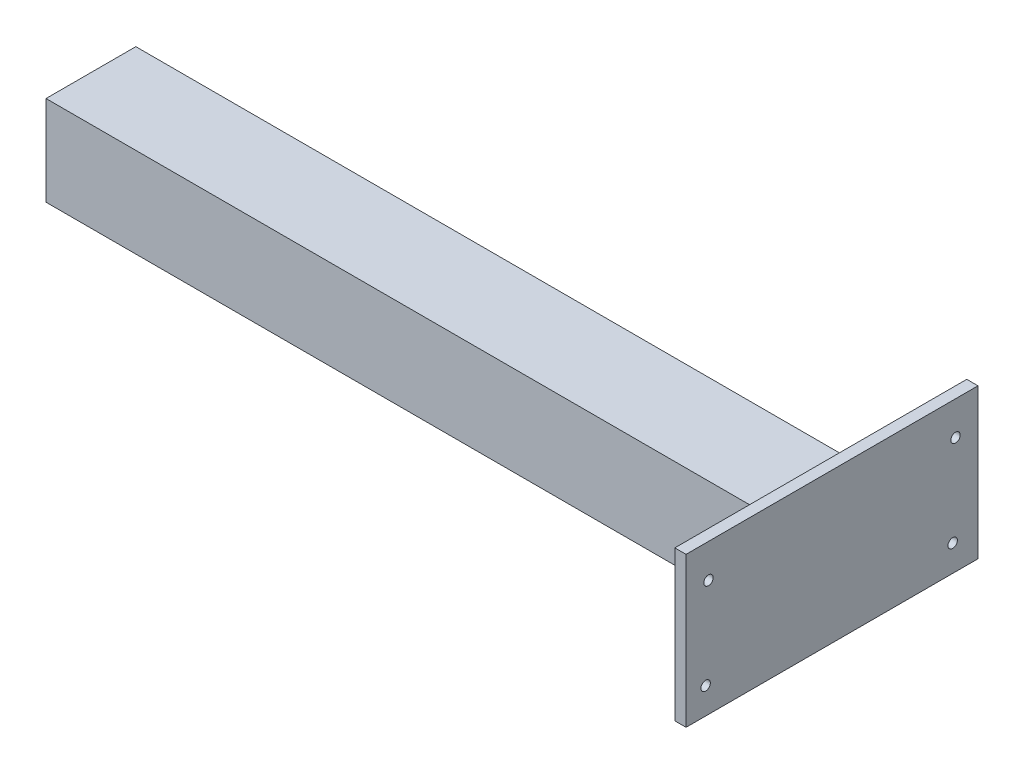
SolidWorks part; units mm, degrees
ref_plane "前视基准面" through (0, 0, 0) normal (0, 0, 1) x (1, 0, 0)
ref_plane "上视基准面" through (0, 0, 0) normal (0, 1, 0) x (1, 0, 0)
ref_plane "右视基准面" through (0, 0, 0) normal (1, 0, 0) x (0, 0, -1)
other "Configuration Table"
sketch "草图1" plane through (0, 0, 0) normal (0, 0, 1) x (1, 0, 0)
  line L1 (-200, 20) -> (200, 20)
  line L2 (-200, 20) -> (-200, -20)
  line L3 (-200, -20) -> (200, -20)
  line L4 (200, 20) -> (200, -20)
  line L5 (-200, 20) -> (200, -20) construction
  line L6 (-200, -20) -> (200, 20) construction
  point P0 (0, 0)
  dimension "D1" = 400
  dimension "D2" = 40
extrude "凸台-拉伸1" add sketch "草图1" against normal blind 40
sketch "草图2" plane through (200, 0, 0) normal (1, 0, 0) x (0, 0, -1)
  line L5 (40, -20) -> (40, 20) construction
  line L6 (40, -10) -> (51, -10)
  line L9 (46, -5) -> (51, -5)
  line L10 (46, -5) -> (46, -10)
  line L11 (46, -10) -> (51, -10)
  line L12 (51, -5) -> (51, -10)
  line L13 (46, -5) -> (51, -10) construction
  line L14 (46, -10) -> (51, -5) construction
  line L20 (40, -10) -> (40, -20)
  line L21 (40, -20) -> (51, -20)
  line L22 (51, -10) -> (51, -20)
  line L23 (40, -10) -> (51, -20) construction
  line L24 (40, -20) -> (51, -10) construction
  line L25 (40, -20) -> (0, -20) construction
  point P0 (45.5, -15)
  point P12 (48.5, -7.5)
  dimension "D1" = 11
  dimension "D2" = 10
  dimension "D3" = 5
  dimension "D4" = 5
extrude "凸台-拉伸2" add sketch "草图2" against normal blind 400 contours L20 L6 L22 L21
sketch "草图10" plane through (200, 0, 0) normal (1, 0, 0) x (0, 0, -1)
  line L0 (0, 20) -> (20, 20)
  line L1 (40, 20) -> (0, 20) construction
  line L2 (20, 20) -> (20, 0)
  line L3 (20, 0) -> (70, 0)
  line L4 (70, 0) -> (70, 46.72)
  line L5 (70, 0) -> (70, -47.28)
  line L6 (70, -47.28) -> (-60, -47.28)
  line L7 (-60, -47.28) -> (-60, 46.72)
  line L8 (-60, 46.72) -> (70, 46.72)
extrude "凸台-拉伸4" add sketch "草图10" along normal blind 5 contours L5 L6 L7 L8 L4
sketch "草图12" plane through (200, 0, 0) normal (-1, 0, 0) x (0, 0, 1)
  line L0 (60, 46.72) -> (10, 46.72)
  line L2 (60, 46.72) -> (-70, 46.72) construction
  line L6 (10, 46.72) -> (10, 1.72)
  line L7 (10, 1.72) -> (50, 1.72)
  line L8 (50, 1.72) -> (50, 31.72)
  line L9 (50, 1.72) -> (50, -28.28)
  line L10 (50, -28.28) -> (-60, -28.28)
  line L11 (50, 31.72) -> (-60, 31.72)
  circle A0 centre (10, 1.72) radius 2.0061
  circle A1 centre (-60, 31.72) radius 2.017
  point P7 (50, 31.72)
  point P11 (50, -28.28)
  point P12 (-60, -28.28)
  point P13 (-60, 31.72)
hole_wizard "Ø4.2 (4.2) 直径孔1" positions "草图12" profile "草图13" hole size "Ø4.2" standard "ISO" end condition through all
sketch "草图13" plane through (200, 31.72, -60) normal (0, 1, 0) x (0, 0, 1)
  line L0 (0, 0) -> (0, 5)
  line L1 (0, 5) -> (2.1, 5)
  line L2 (2.1, 5) -> (2.1, 0)
  line L5 (2.1, 0) -> (0, 0)
  line L11 (0, -6.35) -> (0, 107.95) construction
  dimension "通孔孔直径" = 4.2
  dimension "通孔孔深度" = 5
sketch "草图17" plane through (0, 0, 0) normal (0, 0, 1) x (1, 0, 0)
  line L0 (-200, 20) -> (-150, 20)
  line L1 (200, 20) -> (-200, 20) construction
  line L2 (-150, 20) -> (-150, -20)
  line L3 (-200, -20) -> (200, -20) construction
  line L4 (-150, -20) -> (-200, -20)
  line L5 (-200, -20) -> (-200, 20)
extrude "切除-拉伸5" cut sketch "草图17" against normal blind 50
sketch "草图22" plane through (200, 0, 0) normal (-1, 0, 0) x (0, 0, 1)
  line L0 (-70, -20.1264) -> (60, -20.1264)
  line L1 (-70, 46.72) -> (-70, -47.28) construction
  line L2 (-70, -20.1264) -> (-70, -47.28)
  line L3 (-70, -47.28) -> (60, -47.28)
  line L4 (60, -47.28) -> (60, -20.1264)
extrude "切除-拉伸11" cut sketch "草图22" against normal blind 10
hole_wizard "Ø1.0 (4.2) 直径孔1" positions "草图25" profile "草图26" hole size "Ø1.0" standard "ISO" end condition through all
sketch "草图25" plane through (200, 0, 0) normal (-1, 0, 0) x (0, 0, 1)
  point P0 (51.2755, -8.28)
  point P2 (50, 31.72)
  point P5 (-60, 31.72)
  point P8 (-58.7245, -8.28)
  dimension "D1" = 40
  dimension "D2" = 40
  dimension "D3" = 110
sketch "草图26" plane through (200, -8.28, 51.2755) normal (0, 1, 0) x (0, 0, 1)
  line L0 (0, 0) -> (0, 5)
  line L1 (0, 5) -> (2.1, 5)
  line L2 (2.1, 5) -> (2.1, 0)
  line L5 (2.1, 0) -> (0, 0)
  line L11 (0, -6.35) -> (0, 107.95) construction
  dimension "通孔孔直径" = 4.2
  dimension "通孔孔深度" = 5
sketch "草图30" plane through (0, -10, 0) normal (0, 1, 0) x (1, 0, 0)
  line L0 (-150, 50) -> (-150, 51)
  line L1 (-200, 51) -> (200, 51) construction
  line L2 (-150, 51) -> (-200, 51)
  line L3 (-200, 51) -> (-200, 50)
  line L4 (-200, 50) -> (-150, 50) construction
  line L5 (-200, 50) -> (-150, 50)
extrude "切除-拉伸13" cut sketch "草图30" against normal blind 10
sketch "草图31" plane through (200, 0, 0) normal (-1, 0, 0) x (0, 0, 1)
  line L4 (-51, -10) -> (-43, -10)
  line L5 (-51, -10) -> (-51, 0)
  line L7 (-40, -10) -> (-51, -10) construction
  line L8 (-43, -10) -> (-43, 0)
  line L9 (-43, 0) -> (-51, 0)
extrude "凸台-拉伸6" add sketch "草图31" along normal blind 350
sketch "草图32" plane through (0, 0, -51) normal (0, 0, -1) x (-1, 0, 0)
  line L1 (-65.3449, -4.7056) -> (-63.3449, -4.7056)
  line L3 (-198.5883, -4.7056) -> (-196.5883, -4.7056)
  line L4 (-200, 0) -> (-195.1766, 0)
  line L5 (150, 0) -> (-200, 0) construction
  line L6 (-195.1766, 0) -> (-196.5883, -4.7056)
  line L7 (-198.5883, -4.7056) -> (-200, 0)
  line L8 (-191.5346, -4.7056) -> (-189.5346, -4.7056)
  line L9 (-188.1229, 0) -> (-189.5346, -4.7056)
  line L10 (-192.9463, 0) -> (-188.1229, 0)
  line L11 (-191.5346, -4.7056) -> (-192.9463, 0)
  line L12 (-184.5256, -4.7056) -> (-182.5256, -4.7056)
  line L13 (-181.114, 0) -> (-182.5256, -4.7056)
  line L14 (-185.9373, 0) -> (-181.114, 0)
  line L15 (-184.5256, -4.7056) -> (-185.9373, 0)
  line L16 (-177.4719, -4.7056) -> (-175.4719, -4.7056)
  line L17 (-174.0602, 0) -> (-175.4719, -4.7056)
  line L18 (-178.8836, 0) -> (-174.0602, 0)
  line L19 (-177.4719, -4.7056) -> (-178.8836, 0)
  line L20 (-156.49, -4.7056) -> (-154.49, -4.7056)
  line L21 (-153.0783, 0) -> (-154.49, -4.7056)
  line L22 (-157.9017, 0) -> (-153.0783, 0)
  line L23 (-156.49, -4.7056) -> (-157.9017, 0)
  line L24 (-163.4989, -4.7056) -> (-161.4989, -4.7056)
  line L25 (-160.0873, 0) -> (-161.4989, -4.7056)
  line L26 (-164.9106, 0) -> (-160.0873, 0)
  line L27 (-163.4989, -4.7056) -> (-164.9106, 0)
  line L28 (-170.5527, -4.7056) -> (-168.5527, -4.7056)
  line L29 (-167.141, 0) -> (-168.5527, -4.7056)
  line L30 (-171.9644, 0) -> (-167.141, 0)
  line L31 (-170.5527, -4.7056) -> (-171.9644, 0)
  line L32 (-149.4363, -4.7056) -> (-147.4363, -4.7056)
  line L33 (-146.0246, 0) -> (-147.4363, -4.7056)
  line L34 (-150.848, 0) -> (-146.0246, 0)
  line L35 (-149.4363, -4.7056) -> (-150.848, 0)
  line L36 (-121.4206, -4.7056) -> (-119.4206, -4.7056)
  line L37 (-118.0089, 0) -> (-119.4206, -4.7056)
  line L38 (-122.8323, 0) -> (-118.0089, 0)
  line L39 (-121.4206, -4.7056) -> (-122.8323, 0)
  line L40 (-128.4743, -4.7056) -> (-126.4743, -4.7056)
  line L41 (-125.0626, 0) -> (-126.4743, -4.7056)
  line L42 (-129.886, 0) -> (-125.0626, 0)
  line L43 (-128.4743, -4.7056) -> (-129.886, 0)
  line L44 (-135.4833, -4.7056) -> (-133.4833, -4.7056)
  line L45 (-132.0716, 0) -> (-133.4833, -4.7056)
  line L46 (-136.8949, 0) -> (-132.0716, 0)
  line L47 (-135.4833, -4.7056) -> (-136.8949, 0)
  line L48 (-142.537, -4.7056) -> (-140.537, -4.7056)
  line L49 (-139.1253, 0) -> (-140.537, -4.7056)
  line L50 (-143.9487, 0) -> (-139.1253, 0)
  line L51 (-142.537, -4.7056) -> (-143.9487, 0)
  line L52 (-93.3984, -4.7056) -> (-91.3984, -4.7056)
  line L53 (-89.9867, 0) -> (-91.3984, -4.7056)
  line L54 (-94.8101, 0) -> (-89.9867, 0)
  line L55 (-93.3984, -4.7056) -> (-94.8101, 0)
  line L56 (-100.4522, -4.7056) -> (-98.4522, -4.7056)
  line L57 (-97.0405, 0) -> (-98.4522, -4.7056)
  line L58 (-101.8638, 0) -> (-97.0405, 0)
  line L59 (-100.4522, -4.7056) -> (-101.8638, 0)
  line L60 (-107.4611, -4.7056) -> (-105.4611, -4.7056)
  line L61 (-104.0494, 0) -> (-105.4611, -4.7056)
  line L62 (-108.8728, 0) -> (-104.0494, 0)
  line L63 (-107.4611, -4.7056) -> (-108.8728, 0)
  line L64 (-114.5148, -4.7056) -> (-112.5148, -4.7056)
  line L65 (-111.1031, 0) -> (-112.5148, -4.7056)
  line L66 (-115.9265, 0) -> (-111.1031, 0)
  line L67 (-114.5148, -4.7056) -> (-115.9265, 0)
  line L68 (-61.9332, 0) -> (-63.3449, -4.7056)
  line L69 (-66.7566, 0) -> (-61.9332, 0)
  line L70 (-65.3449, -4.7056) -> (-66.7566, 0)
  line L71 (-72.3986, -4.7056) -> (-70.3986, -4.7056)
  line L72 (-68.9869, 0) -> (-70.3986, -4.7056)
  line L73 (-73.8103, 0) -> (-68.9869, 0)
  line L74 (-72.3986, -4.7056) -> (-73.8103, 0)
  line L75 (-79.4076, -4.7056) -> (-77.4076, -4.7056)
  line L76 (-75.9959, 0) -> (-77.4076, -4.7056)
  line L77 (-80.8192, 0) -> (-75.9959, 0)
  line L78 (-79.4076, -4.7056) -> (-80.8192, 0)
  line L79 (-86.4613, -4.7056) -> (-84.4613, -4.7056)
  line L80 (-83.0496, 0) -> (-84.4613, -4.7056)
  line L81 (-87.873, 0) -> (-83.0496, 0)
  line L82 (-86.4613, -4.7056) -> (-87.873, 0)
  line L83 (-37.0463, -4.7056) -> (-35.0463, -4.7056)
  line L84 (-33.6346, 0) -> (-35.0463, -4.7056)
  line L85 (-38.458, 0) -> (-33.6346, 0)
  line L86 (-37.0463, -4.7056) -> (-38.458, 0)
  line L87 (-44.1001, -4.7056) -> (-42.1001, -4.7056)
  line L88 (-40.6884, 0) -> (-42.1001, -4.7056)
  line L89 (-45.5118, 0) -> (-40.6884, 0)
  line L90 (-44.1001, -4.7056) -> (-45.5118, 0)
  line L91 (-51.109, -4.7056) -> (-49.109, -4.7056)
  line L92 (-47.6973, 0) -> (-49.109, -4.7056)
  line L93 (-52.5207, 0) -> (-47.6973, 0)
  line L94 (-51.109, -4.7056) -> (-52.5207, 0)
  line L95 (-58.1627, -4.7056) -> (-56.1627, -4.7056)
  line L96 (-54.751, 0) -> (-56.1627, -4.7056)
  line L97 (-59.5744, 0) -> (-54.751, 0)
  line L98 (-58.1627, -4.7056) -> (-59.5744, 0)
  line L99 (-30.1435, -4.7056) -> (-28.1435, -4.7056)
  line L100 (-26.7318, 0) -> (-28.1435, -4.7056)
  line L101 (-31.5552, 0) -> (-26.7318, 0)
  line L102 (-30.1435, -4.7056) -> (-31.5552, 0)
  line L103 (-23.0897, -4.7056) -> (-21.0897, -4.7056)
  line L104 (-19.6781, 0) -> (-21.0897, -4.7056)
  line L105 (-24.5014, 0) -> (-19.6781, 0)
  line L106 (-23.0897, -4.7056) -> (-24.5014, 0)
  line L107 (-16.0808, -4.7056) -> (-14.0808, -4.7056)
  line L108 (-12.6691, 0) -> (-14.0808, -4.7056)
  line L109 (-17.4925, 0) -> (-12.6691, 0)
  line L110 (-16.0808, -4.7056) -> (-17.4925, 0)
  line L111 (-9.0271, -4.7056) -> (-7.0271, -4.7056)
  line L112 (-5.6154, 0) -> (-7.0271, -4.7056)
  line L113 (-10.4388, 0) -> (-5.6154, 0)
  line L114 (-9.0271, -4.7056) -> (-10.4388, 0)
  line L115 (-2.158, -4.7056) -> (-0.158, -4.7056)
  line L116 (1.2537, 0) -> (-0.158, -4.7056)
  line L117 (-3.5697, 0) -> (1.2537, 0)
  line L118 (-2.158, -4.7056) -> (-3.5697, 0)
  line L119 (4.8958, -4.7056) -> (6.8958, -4.7056)
  line L120 (8.3074, 0) -> (6.8958, -4.7056)
  line L121 (3.4841, 0) -> (8.3074, 0)
  line L122 (4.8958, -4.7056) -> (3.4841, 0)
  line L123 (11.9047, -4.7056) -> (13.9047, -4.7056)
  line L124 (15.3164, 0) -> (13.9047, -4.7056)
  line L125 (10.493, 0) -> (15.3164, 0)
  line L126 (11.9047, -4.7056) -> (10.493, 0)
  line L127 (18.9584, -4.7056) -> (20.9584, -4.7056)
  line L128 (22.3701, 0) -> (20.9584, -4.7056)
  line L129 (17.5467, 0) -> (22.3701, 0)
  line L130 (18.9584, -4.7056) -> (17.5467, 0)
  line L131 (46.9794, -4.7056) -> (48.9794, -4.7056)
  line L132 (50.3911, 0) -> (48.9794, -4.7056)
  line L133 (45.5677, 0) -> (50.3911, 0)
  line L134 (46.9794, -4.7056) -> (45.5677, 0)
  line L135 (39.9256, -4.7056) -> (41.9256, -4.7056)
  line L136 (43.3373, 0) -> (41.9256, -4.7056)
  line L137 (38.5139, 0) -> (43.3373, 0)
  line L138 (39.9256, -4.7056) -> (38.5139, 0)
  line L139 (32.9167, -4.7056) -> (34.9167, -4.7056)
  line L140 (36.3284, 0) -> (34.9167, -4.7056)
  line L141 (31.505, 0) -> (36.3284, 0)
  line L142 (32.9167, -4.7056) -> (31.505, 0)
  line L143 (25.863, -4.7056) -> (27.863, -4.7056)
  line L144 (29.2747, 0) -> (27.863, -4.7056)
  line L145 (24.4513, 0) -> (29.2747, 0)
  line L146 (25.863, -4.7056) -> (24.4513, 0)
  line L147 (74.9845, -4.7056) -> (76.9845, -4.7056)
  line L148 (78.3962, 0) -> (76.9845, -4.7056)
  line L149 (73.5728, 0) -> (78.3962, 0)
  line L150 (74.9845, -4.7056) -> (73.5728, 0)
  line L151 (67.9308, -4.7056) -> (69.9308, -4.7056)
  line L152 (71.3425, 0) -> (69.9308, -4.7056)
  line L153 (66.5191, 0) -> (71.3425, 0)
  line L154 (67.9308, -4.7056) -> (66.5191, 0)
  line L155 (60.9219, -4.7056) -> (62.9219, -4.7056)
  line L156 (64.3335, 0) -> (62.9219, -4.7056)
  line L157 (59.5102, 0) -> (64.3335, 0)
  line L158 (60.9219, -4.7056) -> (59.5102, 0)
  line L159 (53.8681, -4.7056) -> (55.8681, -4.7056)
  line L160 (57.2798, 0) -> (55.8681, -4.7056)
  line L161 (52.4564, 0) -> (57.2798, 0)
  line L162 (53.8681, -4.7056) -> (52.4564, 0)
  line L163 (103.0037, -4.7056) -> (105.0037, -4.7056)
  line L164 (106.4154, 0) -> (105.0037, -4.7056)
  line L165 (101.5921, 0) -> (106.4154, 0)
  line L166 (103.0037, -4.7056) -> (101.5921, 0)
  line L167 (95.95, -4.7056) -> (97.95, -4.7056)
  line L168 (99.3617, 0) -> (97.95, -4.7056)
  line L169 (94.5383, 0) -> (99.3617, 0)
  line L170 (95.95, -4.7056) -> (94.5383, 0)
  line L171 (88.9411, -4.7056) -> (90.9411, -4.7056)
  line L172 (92.3528, 0) -> (90.9411, -4.7056)
  line L173 (87.5294, 0) -> (92.3528, 0)
  line L174 (88.9411, -4.7056) -> (87.5294, 0)
  line L175 (81.8873, -4.7056) -> (83.8873, -4.7056)
  line L176 (85.299, 0) -> (83.8873, -4.7056)
  line L177 (80.4756, 0) -> (85.299, 0)
  line L178 (81.8873, -4.7056) -> (80.4756, 0)
  line L179 (131.0756, -4.7056) -> (133.0756, -4.7056)
  line L180 (134.4873, 0) -> (133.0756, -4.7056)
  line L181 (129.6639, 0) -> (134.4873, 0)
  line L182 (131.0756, -4.7056) -> (129.6639, 0)
  line L183 (124.0219, -4.7056) -> (126.0219, -4.7056)
  line L184 (127.4336, 0) -> (126.0219, -4.7056)
  line L185 (122.6102, 0) -> (127.4336, 0)
  line L186 (124.0219, -4.7056) -> (122.6102, 0)
  line L187 (117.0129, -4.7056) -> (119.0129, -4.7056)
  line L188 (120.4246, 0) -> (119.0129, -4.7056)
  line L189 (115.6013, 0) -> (120.4246, 0)
  line L190 (117.0129, -4.7056) -> (115.6013, 0)
  line L191 (109.9592, -4.7056) -> (111.9592, -4.7056)
  line L192 (113.3709, 0) -> (111.9592, -4.7056)
  line L193 (108.5475, 0) -> (113.3709, 0)
  line L194 (109.9592, -4.7056) -> (108.5475, 0)
  line L195 (138.0756, -4.7056) -> (140.0756, -4.7056)
  line L196 (141.4873, 0) -> (140.0756, -4.7056)
  line L197 (136.6639, 0) -> (141.4873, 0)
  line L198 (138.0756, -4.7056) -> (136.6639, 0)
  line L199 (145.0756, -4.7056) -> (147.0756, -4.7056)
  line L200 (148.4873, 0) -> (147.0756, -4.7056)
  line L201 (143.6639, 0) -> (148.4873, 0)
  line L202 (145.0756, -4.7056) -> (143.6639, 0)
  line L207 (152.0756, -4.7056) -> (154.0756, -4.7056) [skipped]
  line L208 (155.4873, 0) -> (154.0756, -4.7056) [skipped]
  line L209 (150.6639, 0) -> (155.4873, 0) [skipped]
  line L210 (152.0756, -4.7056) -> (150.6639, 0) [skipped]
  dimension "D1" = 2
  dimension "D2" = 2
  dimension "D3" = 2
  dimension "D4" = 2
  dimension "D5" = 2
  dimension "D6" = 2
  dimension "D7" = 2
  dimension "D8" = 2
  dimension "D9" = 2
  dimension "D10" = 2
  dimension "D11" = 2
  dimension "D12" = 2
  dimension "D13" = 2
  dimension "D14" = 2
  dimension "D15" = 2
extrude "切除-拉伸16" cut sketch "草图32" against normal blind 8
sketch "草图33" plane through (-150, 0, 0) normal (-1, 0, 0) x (0, 0, 1)
  line L0 (-40, 20) -> (0, 20)
  line L1 (0, 20) -> (0, -20)
  line L2 (0, -20) -> (-51, -20)
  line L3 (-51, -20) -> (-51, 0)
  line L4 (-51, 0) -> (-43, 0)
  line L5 (-43, 0) -> (-43, -10)
  line L6 (-43, -10) -> (-40, -10)
  line L7 (-43, -10) -> (-40, -10) construction
  line L8 (-40, -10) -> (-43, -10) construction
  line L9 (-40, -10) -> (-40, 20)
extrude "切除-拉伸17" cut sketch "草图33" against normal blind 5 contours L9 L0 L1 L2 L3 L4 L5 L6
sketch "草图34" plane through (0, 0, -51) normal (0, 0, -1) x (-1, 0, 0)
  line L0 (-200, 0) -> (145, 0)
  line L1 (-200, -10) -> (-200, 20) construction
  line L2 (145, -10) -> (145, 20) construction
  line L3 (-200, 0) -> (-200, -8.7185)
  line L4 (-200, 0) -> (-200, -20) construction
  line L5 (-200, -8.7185) -> (145, -8.7185)
  line L6 (145, -20) -> (145, -4.4536) construction
  line L7 (145, -8.7185) -> (145, 0)
extrude "切除-拉伸18" cut sketch "草图34" against normal blind 10
sketch "草图36" plane through (-145, 0, 0) normal (-1, 0, 0) x (0, 0, 1)
  line L0 (-43, -10) -> (-51, -10)
  line L1 (-51, -8.7185) -> (-51, -20) construction
  line L2 (-51, -10) -> (-51, -8.7185)
  line L3 (-51, -8.7185) -> (-43, -8.7185)
  line L4 (-43, -8.7185) -> (-43, -10)
extrude "切除-拉伸19" cut sketch "草图36" against normal blind 345
ref_plane "基准面12" through (200, -20, -51) normal (1, 0, 0) x (0, 0, -1)
sketch "草图47" plane through (200, -20, -51) normal (1, 0, 0) x (0, 0, -1)
  line L0 (0, 10) -> (-11, 10)
  line L1 (-11, 10) -> (-11, 0)
  line L2 (-51, 0) -> (0, 0) construction
  line L3 (-11, 0) -> (0, 0)
  line L4 (0, 0) -> (0, 10)
extrude "切除-拉伸25" cut sketch "草图47" against normal blind 345
sketch "草图48" plane through (200, 0, 0) normal (-1, 0, 0) x (0, 0, 1)
  line L0 (-40, -20) -> (-54, -20)
  line L2 (-54, -20) -> (-54, -10)
  line L3 (-54, -10) -> (-40, -10)
  line L4 (-40, -20) -> (-40, 20) construction
  line L5 (-40, -10) -> (-40, -20)
extrude "凸台-拉伸16" add sketch "草图48" along normal blind 345
sketch "草图50" plane through (200, 0, 0) normal (-1, 0, 0) x (0, 0, 1)
  line L0 (-54, -10) -> (-46, -10)
  line L1 (-40, -10) -> (-54, -10) construction
  line L2 (-46, -10) -> (-46, 0)
  line L3 (-46, 0) -> (-54, 0)
  line L4 (-54, 0) -> (-54, -10)
extrude "凸台-拉伸17" add sketch "草图50" along normal blind 345
sketch "草图51" plane through (0, 0, -54) normal (0, 0, -1) x (-1, 0, 0)
  line L0 (-200, 0) -> (-195, 0)
  line L1 (-200, 35) -> (-200, -75) construction
  line L2 (145, 0) -> (-200, 0) construction
  line L5 (-196.5, -5) -> (-198.5091, -5)
  line L6 (-198.5091, -5) -> (-200, 0)
  line L7 (-196.5, -5) -> (-195, 0)
  line L8 (-192.9724, 0) -> (-187.9724, 0)
  line L9 (-189.4724, -5) -> (-187.9724, 0)
  line L10 (-189.4724, -5) -> (-191.4815, -5)
  line L11 (-191.4815, -5) -> (-192.9724, 0)
  line L12 (-178.9553, 0) -> (-173.9553, 0)
  line L13 (-175.4553, -5) -> (-173.9553, 0)
  line L14 (-175.4553, -5) -> (-177.4644, -5)
  line L15 (-177.4644, -5) -> (-178.9553, 0)
  line L16 (-185.9829, 0) -> (-180.9829, 0)
  line L17 (-182.4829, -5) -> (-180.9829, 0)
  line L18 (-182.4829, -5) -> (-184.492, -5)
  line L19 (-184.492, -5) -> (-185.9829, 0)
  line L20 (-150.9126, 0) -> (-145.9126, 0)
  line L21 (-147.4126, -5) -> (-145.9126, 0)
  line L22 (-147.4126, -5) -> (-149.4217, -5)
  line L23 (-149.4217, -5) -> (-150.9126, 0)
  line L24 (-157.9402, 0) -> (-152.9402, 0)
  line L25 (-154.4402, -5) -> (-152.9402, 0)
  line L26 (-154.4402, -5) -> (-156.4493, -5)
  line L27 (-156.4493, -5) -> (-157.9402, 0)
  line L28 (-164.9297, 0) -> (-159.9297, 0)
  line L29 (-161.4297, -5) -> (-159.9297, 0)
  line L30 (-161.4297, -5) -> (-163.4388, -5)
  line L31 (-163.4388, -5) -> (-164.9297, 0)
  line L32 (-171.9573, 0) -> (-166.9573, 0)
  line L33 (-168.4573, -5) -> (-166.9573, 0)
  line L34 (-168.4573, -5) -> (-170.4664, -5)
  line L35 (-170.4664, -5) -> (-171.9573, 0)
  line L36 (-122.9126, 0) -> (-117.9126, 0)
  line L37 (-119.4126, -5) -> (-117.9126, 0)
  line L38 (-119.4126, -5) -> (-121.4217, -5)
  line L39 (-121.4217, -5) -> (-122.9126, 0)
  line L40 (-129.9402, 0) -> (-124.9402, 0)
  line L41 (-126.4402, -5) -> (-124.9402, 0)
  line L42 (-126.4402, -5) -> (-128.4493, -5)
  line L43 (-128.4493, -5) -> (-129.9402, 0)
  line L44 (-136.9297, 0) -> (-131.9297, 0)
  line L45 (-133.4297, -5) -> (-131.9297, 0)
  line L46 (-133.4297, -5) -> (-135.4388, -5)
  line L47 (-135.4388, -5) -> (-136.9297, 0)
  line L48 (-143.9573, 0) -> (-138.9573, 0)
  line L49 (-140.4573, -5) -> (-138.9573, 0)
  line L50 (-140.4573, -5) -> (-142.4664, -5)
  line L51 (-142.4664, -5) -> (-143.9573, 0)
  line L52 (-94.9126, 0) -> (-89.9126, 0)
  line L53 (-91.4126, -5) -> (-89.9126, 0)
  line L54 (-91.4126, -5) -> (-93.4217, -5)
  line L55 (-93.4217, -5) -> (-94.9126, 0)
  line L56 (-101.9402, 0) -> (-96.9402, 0)
  line L57 (-98.4402, -5) -> (-96.9402, 0)
  line L58 (-98.4402, -5) -> (-100.4493, -5)
  line L59 (-100.4493, -5) -> (-101.9402, 0)
  line L60 (-108.9297, 0) -> (-103.9297, 0)
  line L61 (-105.4297, -5) -> (-103.9297, 0)
  line L62 (-105.4297, -5) -> (-107.4388, -5)
  line L63 (-107.4388, -5) -> (-108.9297, 0)
  line L64 (-115.9573, 0) -> (-110.9573, 0)
  line L65 (-112.4573, -5) -> (-110.9573, 0)
  line L66 (-112.4573, -5) -> (-114.4664, -5)
  line L67 (-114.4664, -5) -> (-115.9573, 0)
  line L68 (-66.9126, 0) -> (-61.9126, 0)
  line L69 (-63.4126, -5) -> (-61.9126, 0)
  line L70 (-63.4126, -5) -> (-65.4217, -5)
  line L71 (-65.4217, -5) -> (-66.9126, 0)
  line L72 (-73.9402, 0) -> (-68.9402, 0)
  line L73 (-70.4402, -5) -> (-68.9402, 0)
  line L74 (-70.4402, -5) -> (-72.4493, -5)
  line L75 (-72.4493, -5) -> (-73.9402, 0)
  line L76 (-80.9297, 0) -> (-75.9297, 0)
  line L77 (-77.4297, -5) -> (-75.9297, 0)
  line L78 (-77.4297, -5) -> (-79.4388, -5)
  line L79 (-79.4388, -5) -> (-80.9297, 0)
  line L80 (-87.9573, 0) -> (-82.9573, 0)
  line L81 (-84.4573, -5) -> (-82.9573, 0)
  line L82 (-84.4573, -5) -> (-86.4664, -5)
  line L83 (-86.4664, -5) -> (-87.9573, 0)
  line L84 (-38.9126, 0) -> (-33.9126, 0)
  line L85 (-35.4126, -5) -> (-33.9126, 0)
  line L86 (-35.4126, -5) -> (-37.4217, -5)
  line L87 (-37.4217, -5) -> (-38.9126, 0)
  line L88 (-45.9402, 0) -> (-40.9402, 0)
  line L89 (-42.4402, -5) -> (-40.9402, 0)
  line L90 (-42.4402, -5) -> (-44.4493, -5)
  line L91 (-44.4493, -5) -> (-45.9402, 0)
  line L92 (-52.9297, 0) -> (-47.9297, 0)
  line L93 (-49.4297, -5) -> (-47.9297, 0)
  line L94 (-49.4297, -5) -> (-51.4388, -5)
  line L95 (-51.4388, -5) -> (-52.9297, 0)
  line L96 (-59.9573, 0) -> (-54.9573, 0)
  line L97 (-56.4573, -5) -> (-54.9573, 0)
  line L98 (-56.4573, -5) -> (-58.4664, -5)
  line L99 (-58.4664, -5) -> (-59.9573, 0)
  line L100 (-10.9126, 0) -> (-5.9126, 0)
  line L101 (-7.4126, -5) -> (-5.9126, 0)
  line L102 (-7.4126, -5) -> (-9.4217, -5)
  line L103 (-9.4217, -5) -> (-10.9126, 0)
  line L104 (-17.9402, 0) -> (-12.9402, 0)
  line L105 (-14.4402, -5) -> (-12.9402, 0)
  line L106 (-14.4402, -5) -> (-16.4493, -5)
  line L107 (-16.4493, -5) -> (-17.9402, 0)
  line L108 (-24.9297, 0) -> (-19.9297, 0)
  line L109 (-21.4297, -5) -> (-19.9297, 0)
  line L110 (-21.4297, -5) -> (-23.4388, -5)
  line L111 (-23.4388, -5) -> (-24.9297, 0)
  line L112 (-31.9573, 0) -> (-26.9573, 0)
  line L113 (-28.4573, -5) -> (-26.9573, 0)
  line L114 (-28.4573, -5) -> (-30.4664, -5)
  line L115 (-30.4664, -5) -> (-31.9573, 0)
  line L116 (17.0874, 0) -> (22.0874, 0)
  line L117 (20.5874, -5) -> (22.0874, 0)
  line L118 (20.5874, -5) -> (18.5783, -5)
  line L119 (18.5783, -5) -> (17.0874, 0)
  line L120 (10.0598, 0) -> (15.0598, 0)
  line L121 (13.5598, -5) -> (15.0598, 0)
  line L122 (13.5598, -5) -> (11.5507, -5)
  line L123 (11.5507, -5) -> (10.0598, 0)
  line L124 (3.0703, 0) -> (8.0703, 0)
  line L125 (6.5703, -5) -> (8.0703, 0)
  line L126 (6.5703, -5) -> (4.5612, -5)
  line L127 (4.5612, -5) -> (3.0703, 0)
  line L128 (-3.9573, 0) -> (1.0427, 0)
  line L129 (-0.4573, -5) -> (1.0427, 0)
  line L130 (-0.4573, -5) -> (-2.4664, -5)
  line L131 (-2.4664, -5) -> (-3.9573, 0)
  line L132 (45.0874, 0) -> (50.0874, 0)
  line L133 (48.5874, -5) -> (50.0874, 0)
  line L134 (48.5874, -5) -> (46.5783, -5)
  line L135 (46.5783, -5) -> (45.0874, 0)
  line L136 (38.0598, 0) -> (43.0598, 0)
  line L137 (41.5598, -5) -> (43.0598, 0)
  line L138 (41.5598, -5) -> (39.5507, -5)
  line L139 (39.5507, -5) -> (38.0598, 0)
  line L140 (31.0703, 0) -> (36.0703, 0)
  line L141 (34.5703, -5) -> (36.0703, 0)
  line L142 (34.5703, -5) -> (32.5612, -5)
  line L143 (32.5612, -5) -> (31.0703, 0)
  line L144 (24.0427, 0) -> (29.0427, 0)
  line L145 (27.5427, -5) -> (29.0427, 0)
  line L146 (27.5427, -5) -> (25.5336, -5)
  line L147 (25.5336, -5) -> (24.0427, 0)
  line L148 (73.0874, 0) -> (78.0874, 0)
  line L149 (76.5874, -5) -> (78.0874, 0)
  line L150 (76.5874, -5) -> (74.5783, -5)
  line L151 (74.5783, -5) -> (73.0874, 0)
  line L152 (66.0598, 0) -> (71.0598, 0)
  line L153 (69.5598, -5) -> (71.0598, 0)
  line L154 (69.5598, -5) -> (67.5507, -5)
  line L155 (67.5507, -5) -> (66.0598, 0)
  line L156 (59.0703, 0) -> (64.0703, 0)
  line L157 (62.5703, -5) -> (64.0703, 0)
  line L158 (62.5703, -5) -> (60.5612, -5)
  line L159 (60.5612, -5) -> (59.0703, 0)
  line L160 (52.0427, 0) -> (57.0427, 0)
  line L161 (55.5427, -5) -> (57.0427, 0)
  line L162 (55.5427, -5) -> (53.5336, -5)
  line L163 (53.5336, -5) -> (52.0427, 0)
  line L164 (101.0874, 0) -> (106.0874, 0)
  line L165 (104.5874, -5) -> (106.0874, 0)
  line L166 (104.5874, -5) -> (102.5783, -5)
  line L167 (102.5783, -5) -> (101.0874, 0)
  line L168 (94.0598, 0) -> (99.0598, 0)
  line L169 (97.5598, -5) -> (99.0598, 0)
  line L170 (97.5598, -5) -> (95.5507, -5)
  line L171 (95.5507, -5) -> (94.0598, 0)
  line L172 (87.0703, 0) -> (92.0703, 0)
  line L173 (90.5703, -5) -> (92.0703, 0)
  line L174 (90.5703, -5) -> (88.5612, -5)
  line L175 (88.5612, -5) -> (87.0703, 0)
  line L176 (80.0427, 0) -> (85.0427, 0)
  line L177 (83.5427, -5) -> (85.0427, 0)
  line L178 (83.5427, -5) -> (81.5336, -5)
  line L179 (81.5336, -5) -> (80.0427, 0)
  line L180 (129.0874, 0) -> (134.0874, 0)
  line L181 (132.5874, -5) -> (134.0874, 0)
  line L182 (132.5874, -5) -> (130.5783, -5)
  line L183 (130.5783, -5) -> (129.0874, 0)
  line L184 (122.0598, 0) -> (127.0598, 0)
  line L185 (125.5598, -5) -> (127.0598, 0)
  line L186 (125.5598, -5) -> (123.5507, -5)
  line L187 (123.5507, -5) -> (122.0598, 0)
  line L188 (115.0703, 0) -> (120.0703, 0)
  line L189 (118.5703, -5) -> (120.0703, 0)
  line L190 (118.5703, -5) -> (116.5612, -5)
  line L191 (116.5612, -5) -> (115.0703, 0)
  line L192 (108.0427, 0) -> (113.0427, 0)
  line L193 (111.5427, -5) -> (113.0427, 0)
  line L194 (111.5427, -5) -> (109.5336, -5)
  line L195 (109.5336, -5) -> (108.0427, 0)
  line L196 (143.0874, 0) -> (148.0874, 0)
  line L197 (146.5874, -5) -> (148.0874, 0)
  line L198 (146.5874, -5) -> (144.5783, -5)
  line L199 (144.5783, -5) -> (143.0874, 0)
  line L200 (136.0598, 0) -> (141.0598, 0)
  line L201 (139.5598, -5) -> (141.0598, 0)
  line L202 (139.5598, -5) -> (137.5507, -5)
  line L203 (137.5507, -5) -> (136.0598, 0)
  dimension "D1" = 2
  dimension "D2" = 2
  dimension "D3" = 2
  dimension "D4" = 2
  dimension "D5" = 2
  dimension "D6" = 2
  dimension "D7" = 2
  dimension "D8" = 2
  dimension "D9" = 2
  dimension "D10" = 2
  dimension "D11" = 2
  dimension "D12" = 2
  dimension "D13" = 2
  dimension "D14" = 2
extrude "切除-拉伸26" cut sketch "草图51" against normal blind 8
sketch "草图52" plane through (-145, 0, 0) normal (-1, 0, 0) x (0, 0, 1)
  line L0 (-54, 0) -> (-46, 0)
  line L1 (-46, 0) -> (-46, -10)
  line L2 (-46, -10) -> (-40, -10)
  line L3 (-40, -10) -> (-40, 20)
  line L4 (-40, 20) -> (0, 20)
  line L5 (-40, 20) -> (0, 20) construction
  line L6 (-40, 20) -> (0, 20) construction
  line L7 (0, 20) -> (0, -20)
  line L8 (0, -20) -> (-54, -20)
  line L9 (-54, -20) -> (-54, 0)
extrude "切除-拉伸28" cut sketch "草图52" against normal blind 5
ref_plane "基准面13" through (200, -20.1264, 60) normal (0, 0, -1) x (-1, 0, 0)
sketch "草图54" plane through (200, 0, 0) normal (-1, 0, 0) x (0, 0, 1)
  line L0 (-70, -20.1264) -> (60, -20.1264)
  line L1 (60, 15.6236) -> (60, -55.8764) construction
  line L2 (60, -20.1264) -> (-70, -20.1264) construction
  line L4 (-54, -20) -> (60, -20)
  line L5 (-54, -20) -> (-54, -20.1264)
  line L7 (60, -20) -> (60, -20.1264)
  line L8 (-54, -20) -> (-70, -20)
  line L11 (-70, -20) -> (-70, -20.1264)
  line M11 (-70, -20.1264) -> (60, -20.1264)
  line M14 (-70, 46.72) -> (-70, -20.1264)
extrude "切除-拉伸29" cut sketch "草图54" against normal blind 5 contours L5 L8 M14 M11
